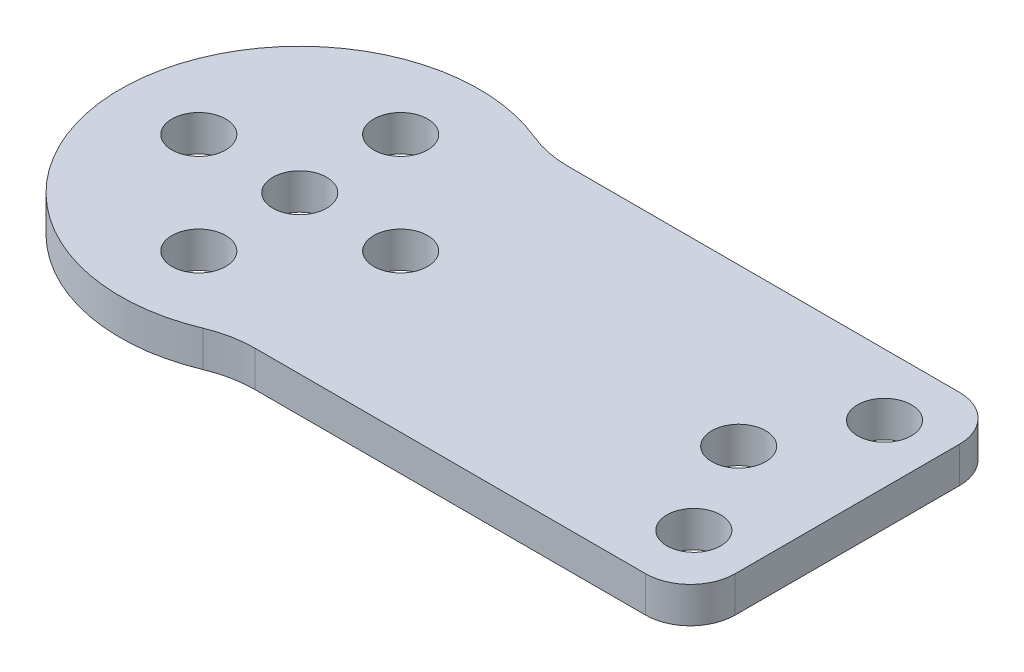
SolidWorks part; units mm, degrees
ref_plane "Front Plane" through (0, 0, 0) normal (0, 0, 1) x (1, 0, 0)
ref_plane "Top Plane" through (0, 0, 0) normal (0, 1, 0) x (1, 0, 0)
ref_plane "Right Plane" through (0, 0, 0) normal (1, 0, 0) x (0, 0, -1)
sketch "Sketch1" plane through (0, 0, 0) normal (0, 1, 0) x (1, 0, 0)
  line L0 (-12.7, 0) -> (12.7, 0) construction
  line L1 (-12.7, -7) -> (12.7, -7) construction
  line L2 (-12.7, 7) -> (12.7, 7) construction
  line L3 (11.7164, 7) -> (-8.827, 7)
  line L4 (-8.827, -7) -> (11.7164, -7)
  line L5 (11.7164, -7) -> (11.7164, 7)
  arc A0 (-8.827, 7) -> (-8.827, -7) centre (-12.7, 0) ccw
  circle A1 centre (-12.7, 0) radius 25.4 construction
  point P3 (0, 0)
  dimension "D1" = 50.8
  dimension "D2" = 16
  dimension "D3" = 7
  dimension "D4" = 7
extrude "Boss-Extrude1" add sketch "Sketch1" along normal mid plane 1.6
fillet "Fillet1" radius 2 2 edges at (11.7164, 0, -7) (11.7164, 0, 7)
fillet "Fillet2" radius 5 2 edges at (-8.827, 0, -7) (-8.827, 0, 7)
sketch "Sketch2" plane through (0, 0.8, 0) normal (0, 1, 0) x (1, 0, 0)
  circle A0 centre (-12.7, 0) radius 4.5 construction
  circle A1 centre (-8.2, 0) radius 1.2
  circle A2 centre (-12.7, 4.5) radius 1.2
  circle A3 centre (-17.2, 0) radius 1.2
  circle A4 centre (-12.7, -4.5) radius 1.2
  circle A5 centre (-12.7, 0) radius 1.2
  dimension "D1" = 2.4
  dimension "D2" = 9
extrude "Cut-Extrude1" cut sketch "Sketch2" against normal through all
sketch "Sketch3" plane through (0, 0.8, 0) normal (0, 1, 0) x (1, 0, 0)
  line L0 (9.1214, 4.25) -> (9.1214, -4.25) construction
  line L1 (9.1214, -4.25) -> (6.8714, 0) construction
  line L2 (6.8714, 0) -> (9.1214, 4.25) construction
  line L3 (11.7164, -5) -> (11.7164, 5) construction
  circle A0 centre (9.1214, 4.25) radius 1.2
  circle A1 centre (9.1214, -4.25) radius 1.2
  circle A2 centre (6.8714, 0) radius 1.2
  dimension "D1" = 2.4
  dimension "D2" = 2.25
  dimension "D3" = 4.25
  dimension "D4" = 2.595
extrude "Cut-Extrude2" cut sketch "Sketch3" against normal through all
sketch "Sketch4" plane through (0, 0.8, 0) normal (0, 1, 0) x (1, 0, 0)
  circle A0 centre (9.1214, 4.25) radius 2.2 construction
  circle A1 centre (6.8714, 0) radius 2.2 construction
  circle A2 centre (9.1214, -4.25) radius 2.2 construction
  dimension "D1" = 4.4
equation "\"D4@Sketch3\"=(7.44-\"D2@Sketch3\")/2"
